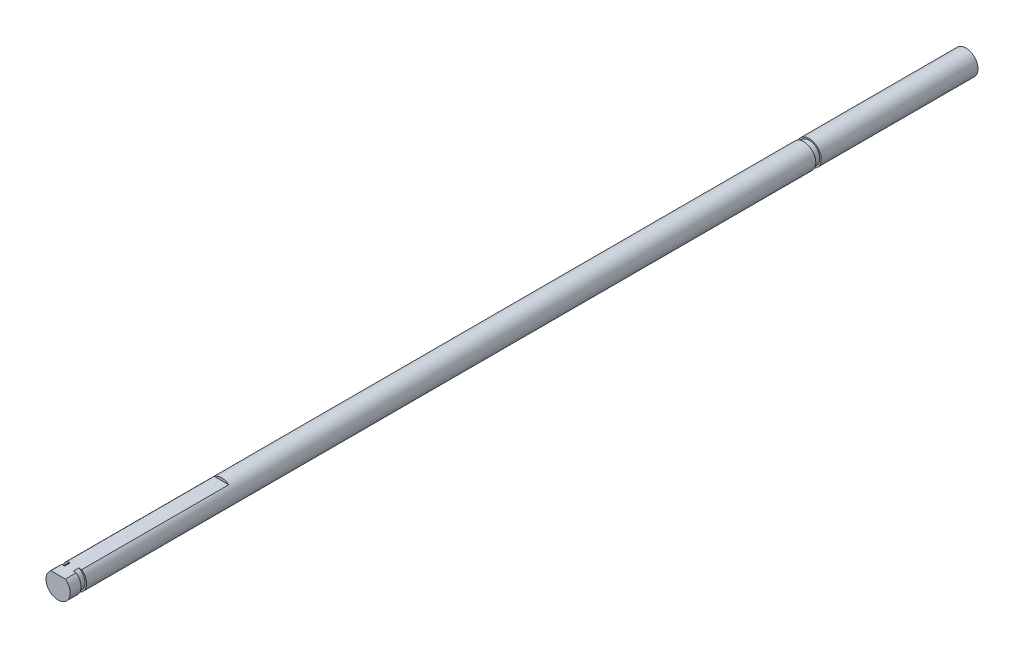
SolidWorks part; units mm, degrees
ref_plane "Vorne" through (0, 0, 0) normal (0, 0, 1) x (1, 0, 0)
ref_plane "Oben" through (0, 0, 0) normal (0, 1, 0) x (1, 0, 0)
ref_plane "Seite" through (0, 0, 0) normal (1, 0, 0) x (0, 0, -1)
sketch "Skizze1" plane through (0, 0, 0) normal (0, 0, 1) x (1, 0, 0)
  circle A0 centre (0, 0) radius 2
  point P3 (0, -3)
  dimension "D1" = 4
  dimension "D2" = 3
extrude "Aufsatz-Linear austragen1" add sketch "Skizze1" along normal mid plane 150
sketch "Skizze2" plane through (0, 0, 75) normal (0, 0, 1) x (1, 0, 0)
  point P0 (0, 0)
sketch "Skizze7" plane through (0, 0, 0) normal (1, 0, 0) x (0, 0, -1)
  line L0 (-73.2, 2) -> (-73.2, 1.75)
  line L1 (75, 2) -> (-75, 2) construction
  line L2 (-73.2, 1.75) -> (-72.3, 1.75)
  line L3 (-72.3, 1.75) -> (-72.3, 2)
  line L4 (-72.3, 2) -> (-73.2, 2)
  line L5 (49.1, 2) -> (49.1, 1.75)
  line L6 (49.1, 1.75) -> (48.2, 1.75)
  line L7 (48.2, 1.75) -> (48.2, 2)
  line L8 (48.2, 2) -> (49.1, 2)
  line L9 (-75, 2) -> (-75, -2) construction
  line L10 (75, 0) -> (-75, 0) construction
  line L11 (75, -2) -> (75, 2) construction
  dimension "D1" = 0.25
  dimension "D2" = 0.9
  dimension "D3" = 1.8
  dimension "D4" = 120.5
revolve "Schnitt-Rotation1" cut sketch "Skizze7" angle 360 about L10
sketch "Skizze8" plane through (0, 0, 75) normal (0, 0, 1) x (1, 0, 0)
  line L0 (1.2, 1.6) -> (-1.2, 1.6)
  line L1 (50, 0) -> (-50, 0) construction
  arc A0 (1.2, 1.6) -> (-1.2, 1.6) centre (0, 0) ccw
  circle A1 centre (0, 0) radius 2 construction
  dimension "D1" = 1.6
extrude "Schnitt-Linear austragen1" cut sketch "Skizze8" against normal blind 27
